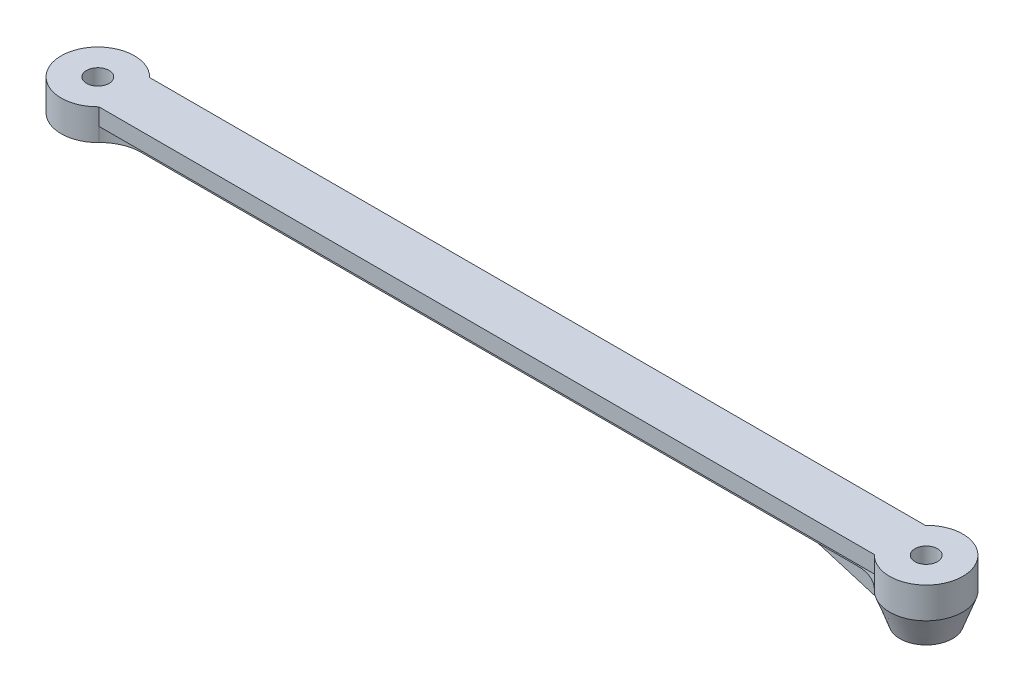
SolidWorks part; units mm, degrees
ref_plane "Front Plane" through (0, 0, 0) normal (0, 0, 1) x (1, 0, 0)
ref_plane "Top Plane" through (0, 0, 0) normal (0, 1, 0) x (1, 0, 0)
ref_plane "Right Plane" through (0, 0, 0) normal (1, 0, 0) x (0, 0, -1)
sketch "Sketch1" plane through (0, 0, 0) normal (0, 1, 0) x (1, 0, 0)
  line L0 (-147, 0) -> (-123.9881, 0) construction
  line L1 (-142.3096, 4.5) -> (-4.6904, 4.5)
  line L3 (-142.3096, -4.5) -> (-4.6904, -4.5)
  circle A0 centre (0, 0) radius 2
  circle A1 centre (-147, 0) radius 2
  arc A3 (-4.6904, -4.5) -> (-4.6904, 4.5) centre (0, 0) ccw
  arc A4 (-142.3096, 4.5) -> (-142.3096, -4.5) centre (-147, 0) ccw
  dimension "D2" = 4
  dimension "D3" = 6.5
  dimension "D1" = 147
  dimension "D4" = 9
extrude "Boss-Extrude1" add sketch "Sketch1" along normal blind 5.5
sketch "Sketch2" plane through (0, 0, 0) normal (0, -1, 0) x (1, 0, 0)
  line L0 (-6.5, 0) -> (-20.7961, 0) construction
  line L1 (-9.9671, 2.25) -> (-137.0329, 2.25)
  line L2 (-73.5, -4.5) -> (-73.5, 2.25) construction
  line L3 (-4.6904, -4.5) -> (-142.3096, -4.5) construction
  line L4 (-9.9671, -2.25) -> (-137.0329, -2.25)
  line L5 (-4.6904, 4.5) -> (-142.3096, 4.5)
  line L6 (-142.3096, -4.5) -> (-4.6904, -4.5)
  arc A0 (-4.6904, 4.5) -> (-9.9671, 2.25) centre (-9.9671, 9.5625) cw
  arc A2 (-142.3096, 4.5) -> (-137.0329, 2.25) centre (-137.0329, 9.5625) ccw
  arc A6 (-4.6904, -4.5) -> (-9.9671, -2.25) centre (-9.9671, -9.5625) ccw
  arc A7 (-4.6904, -4.5) -> (-4.6904, 4.5) centre (0, 0) ccw construction
  arc A8 (-142.3096, -4.5) -> (-137.0329, -2.25) centre (-137.0329, -9.5625) cw
  dimension "D1" = 4.5
extrude "Cut-Extrude1" cut sketch "Sketch2" against normal blind 2.5
ref_plane "Plane1" through (0, -5, 0) normal (0, -1, 0) x (-1, 0, 0)
sketch "Sketch3" plane through (0, -5, 0) normal (0, -1, 0) x (-1, 0, 0)
  circle A0 centre (0, 0) radius 4.68
  arc A1 (4.6904, 4.5) -> (4.6904, -4.5) centre (0, 0) ccw construction
  circle A2 centre (0, 0) radius 2
  circle A3 centre (0, 0) radius 2 construction
  dimension "D1" = 9.36
sketch "Sketch4" plane through (0, 0, 0) normal (0, -1, 0) x (1, 0, 0)
  circle A1 centre (0, 0) radius 6.5
  arc A2 (-4.6904, -4.5) -> (-4.6904, 4.5) centre (0, 0) ccw construction
loft "Loft1" add profiles "Sketch4" section "Sketch4" section "Sketch3"
sketch "Sketch5" plane through (0, -5, 0) normal (0, -1, 0) x (1, 0, 0)
  circle A0 centre (0, 0) radius 2
  circle A1 centre (0, 0) radius 2 construction
extrude "Cut-Extrude2" cut sketch "Sketch5" against normal through all
sketch "Sketch6" plane through (0, 0, 0) normal (0, 0, 1) x (1, 0, 0)
  line L1 (-9.9671, 0) -> (-137.0329, 0) construction
  line L4 (-137.0329, 0) -> (-9.9671, 0) construction
  line L8 (-3.08, 0) -> (-21.28, 0)
  line L11 (-21.28, 0) -> (-4.68, -5)
  line L12 (-4.68, -5) -> (-3.08, -5)
  line L13 (-3.08, -5) -> (-3.08, 0)
  line L14 (-4.68, -5) -> (4.68, -5) construction
  line L15 (-4.68, -5) -> (4.68, -5) construction
  dimension "D1" = 18.2
  dimension "D2" = 1.6
extrude "Boss-Extrude2" add sketch "Sketch6" along normal mid plane 2.5 contours L11 L12 L13 L8
equation "\"Longueur1\"= 135mm"
equation "\"Longueur2\"= 147mm"
equation "\"D1@Sketch1\"=\"Longueur2\""
